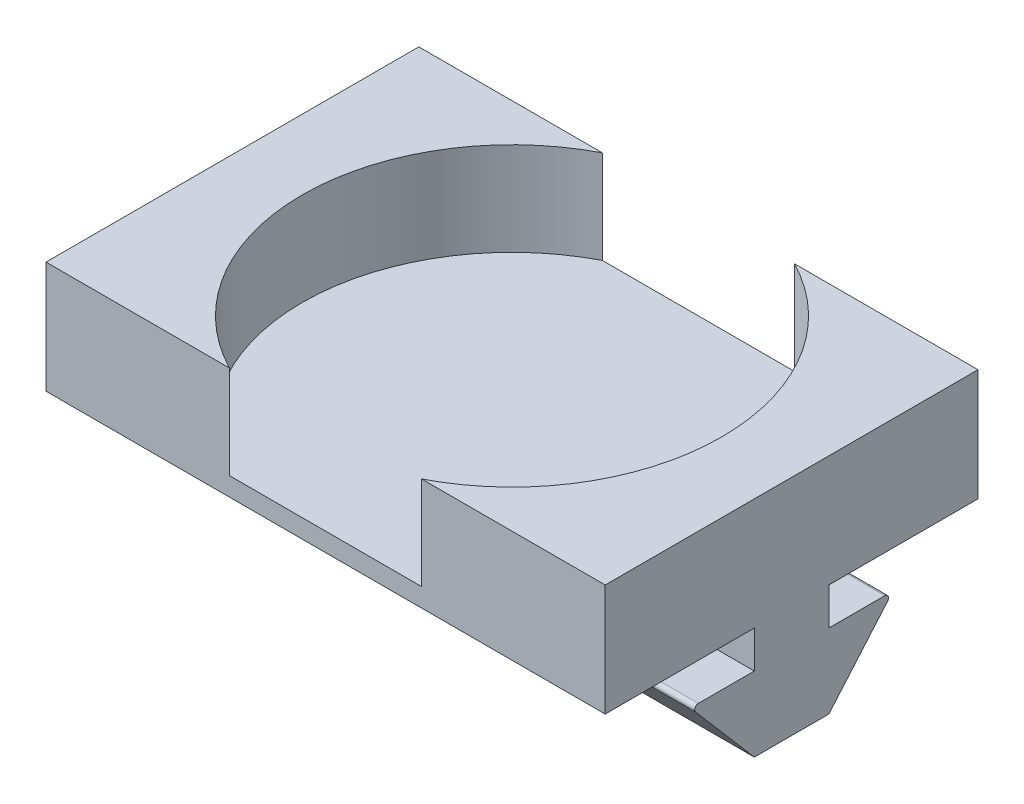
SolidWorks part; units mm, degrees
ref_plane "Front Plane" through (0, 0, 0) normal (0, 0, 1) x (1, 0, 0)
ref_plane "Top Plane" through (0, 0, 0) normal (0, 1, 0) x (1, 0, 0)
ref_plane "Right Plane" through (0, 0, 0) normal (1, 0, 0) x (0, 0, -1)
sketch "Sketch1" plane through (0, 0, 0) normal (0, 1, 0) x (1, 0, 0)
  line L1 (38.1, -25.4) -> (-38.1, -25.4)
  line L2 (38.1, -25.4) -> (38.1, 25.4)
  line L3 (38.1, 25.4) -> (-38.1, 25.4)
  line L4 (-38.1, -25.4) -> (-38.1, 25.4)
  line L5 (38.1, -25.4) -> (-38.1, 25.4) construction
  line L6 (38.1, 25.4) -> (-38.1, -25.4) construction
  point P0 (0, 0)
  dimension "D1" = 76.2
  dimension "D2" = 50.8
sketch "Sketch10" plane through (0, 0, 0) normal (1, 0, 0) x (0, 0, -1)
  line L2 (0, 0) -> (0, 12.7) construction
  line L4 (6.35, 10.16) -> (-6.35, 10.16)
  line L5 (-6.5427, 9.7405) -> (-2.54, 5.08)
  line L6 (6.5427, 9.7405) -> (2.54, 5.08)
  line L7 (2.54, 5.08) -> (-2.54, 5.08)
  line L16 (2.54, 12.7) -> (-2.54, 12.7)
  line L17 (-2.54, 12.7) -> (-2.54, 10.16)
  line L18 (-2.54, 10.16) -> (2.54, 10.16)
  line L19 (2.54, 10.16) -> (2.54, 12.7)
  arc A2 (6.35, 10.16) -> (6.5427, 9.7405) centre (6.35, 9.906) cw
  arc A3 (-6.35, 10.16) -> (-6.5427, 9.7405) centre (-6.35, 9.906) ccw
  point P4 (0, 5.08)
  point P10 (0, 10.16)
  point P35 (0, 12.7)
  dimension "D2" = 5.08
  dimension "D4" = 2.54
  dimension "D6" = 5.08
  dimension "D7" = 12.7
  dimension "D8" = 5.08
extrude "Boss-Extrude3" add sketch "Sketch10" against normal blind 38.1 separate body
sketch "Sketch11" plane through (0, 12.7, 0) normal (0, 1, 0) x (1, 0, 0)
  line L0 (0, -12.7) -> (0, 12.7)
  line L1 (-38.1, -12.7) -> (-38.1, 12.7)
  line L3 (-38.1, 12.7) -> (0, 12.7)
  line L4 (-38.1, -12.7) -> (0, -12.7)
  point P4 (0, 0)
  point P8 (-38.1, 0)
  dimension "D1" = 25.4
extrude "Boss-Extrude4" add sketch "Sketch11" along normal blind 7.62
sketch "Sketch12" plane through (0, 20.32, 0) normal (0, 1, 0) x (1, 0, 0)
  line L0 (0, 0) -> (-38.1, 0) construction
  line L1 (-38.1, 12.7) -> (-38.1, -12.7) construction
  circle A0 centre (-19.05, 0) radius 14.2875
  point P7 (-21.1297, 0)
  dimension "D1" = 28.575
  dimension "D2" = 19.05
extrude "Cut-Extrude1" cut sketch "Sketch12" against normal blind 6.35
